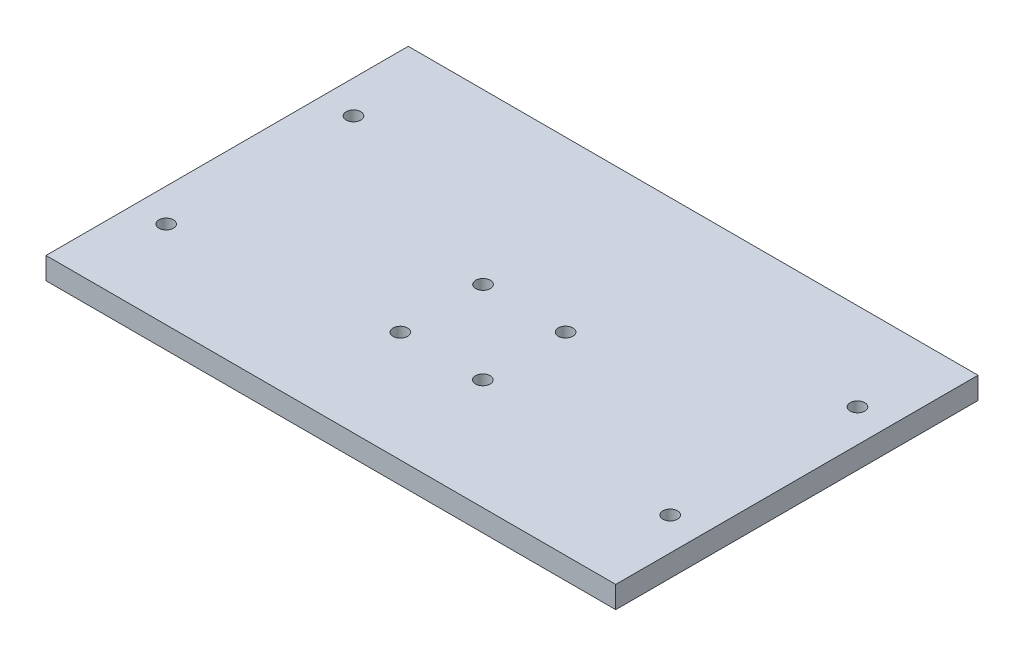
SolidWorks part; units mm, degrees
ref_plane "Front Plane" through (0, 0, 0) normal (0, 0, 1) x (1, 0, 0)
ref_plane "Top Plane" through (0, 0, 0) normal (0, 1, 0) x (1, 0, 0)
ref_plane "Right Plane" through (0, 0, 0) normal (1, 0, 0) x (0, 0, -1)
sketch "Sketch2" plane through (0, 340, 0) normal (0, 1, 0) x (1, 0, 0)
  line L0 (-398.1379, -396.3583) -> (-53.1379, -741.3583) construction
  line L1 (-53.1379, -396.3583) -> (-398.1379, -741.3583) construction
  line L2 (-30.6379, -418.8583) -> (-30.6379, -718.8583) construction
  line L3 (-420.6379, -681.8583) -> (-30.6379, -681.8583)
  line L4 (-420.6379, -681.8583) -> (-420.6379, -455.8583)
  line L6 (-30.6379, -681.8583) -> (-30.6379, -455.8583)
  line L7 (-420.6379, -681.8583) -> (-30.6379, -455.8583) construction
  line L8 (-420.6379, -455.8583) -> (-30.6379, -681.8583) construction
  line L9 (-420.6379, -455.8583) -> (-420.6379, -433.8814)
  line L10 (-420.6379, -718.8583) -> (-420.6379, -418.8583) construction
  line L11 (-420.6379, -433.8814) -> (-30.6379, -433.8814)
  line L12 (-30.6379, -433.8814) -> (-30.6379, -455.8583)
  line L13 (-53.1379, -396.3583) -> (-53.1379, -493.8814) construction
  line L14 (-452.9242, -433.8814) -> (-452.9242, -682.0942) construction
  line L15 (-452.9242, -557.9878) -> (12.3919, -557.9878) construction
  line L16 (-225.6379, -433.8814) -> (-225.6379, -681.8583) construction
  circle A0 centre (-53.1379, -493.8814) radius 5
  circle A1 centre (-53.1379, -622.0942) radius 5
  circle A2 centre (-398.1379, -493.8814) radius 5
  circle A3 centre (-398.1379, -622.0942) radius 5
  circle A4 centre (-197.3844, -549.4512) radius 5 construction
  circle A5 centre (-197.3844, -606.0814) radius 5 construction
  circle A6 centre (-253.8913, -606.0814) radius 5 construction
  circle A7 centre (-253.8913, -549.4512) radius 5 construction
  circle A8 centre (-197.3844, -549.4512) radius 5
  circle A9 centre (-197.3844, -606.0814) radius 5
  circle A10 centre (-253.8913, -606.0814) radius 5
  circle A11 centre (-253.8913, -549.4512) radius 5
  point P8 (-225.6379, -568.8583)
  dimension "D2" = 226
  dimension "D1" = 60
extrude "Boss-Extrude1" add sketch "Sketch2" along normal blind 15
